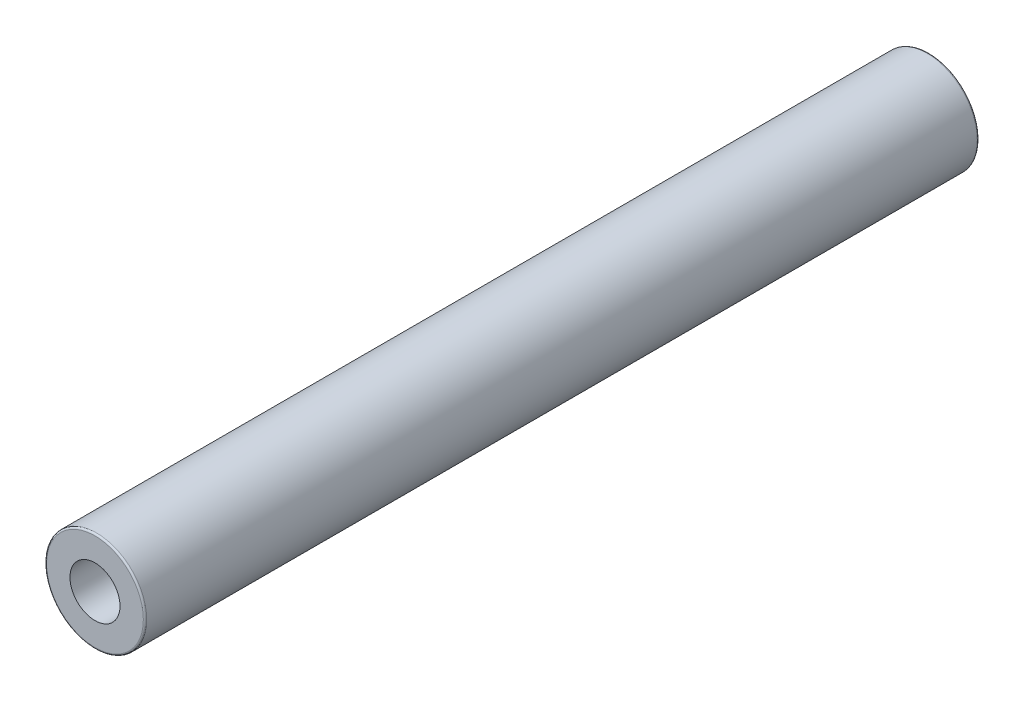
SolidWorks part; units mm, degrees
ref_plane "正面" through (0, 0, 0) normal (0, 0, 1) x (1, 0, 0)
ref_plane "平面" through (0, 0, 0) normal (0, 1, 0) x (1, 0, 0)
ref_plane "右側面" through (0, 0, 0) normal (1, 0, 0) x (0, 0, -1)
sketch "ｽｹｯﾁ1" plane through (0, 0, 0) normal (0, 0, 1) x (1, 0, 0)
  circle A0 centre (0, 0) radius 1.5
  circle A1 centre (0, 0) radius 3
  dimension "D1" = 6
  dimension "D2" = 3
extrude "ﾎﾞｽ - 押し出し1" add sketch "ｽｹｯﾁ1" along normal blind 50
fillet "ﾌｨﾚｯﾄ1" radius 0.1 2 edges at (3, 0, 0) (3, 0, 50)
